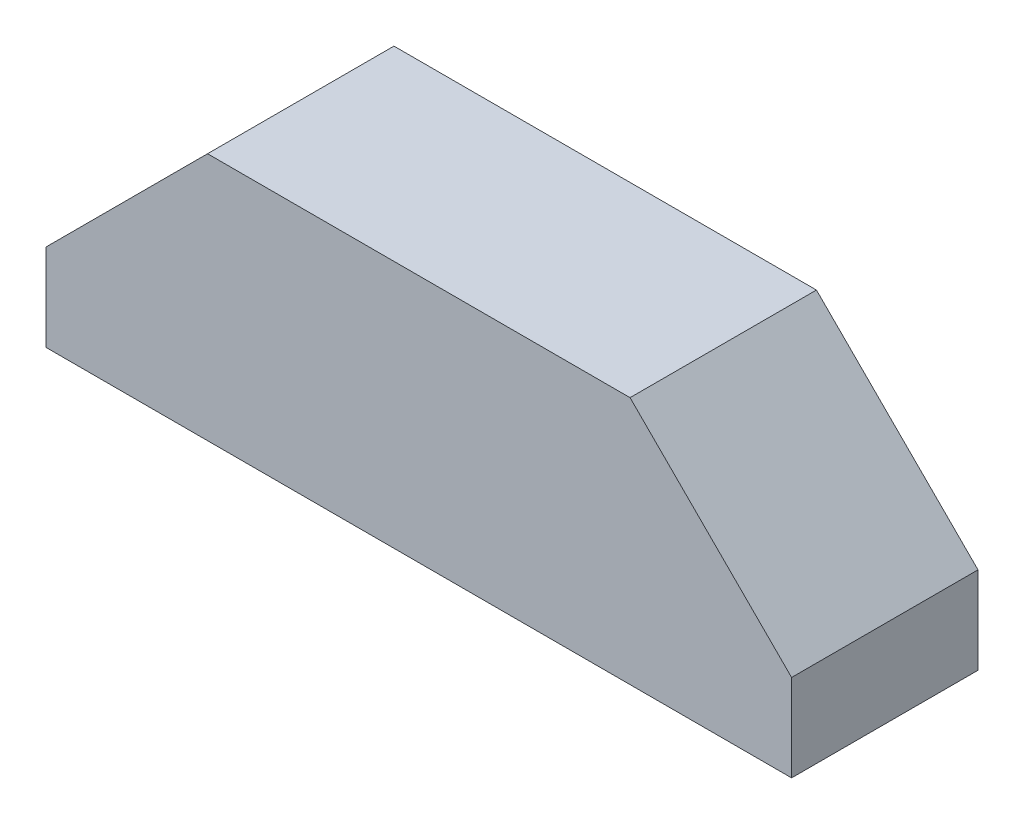
SolidWorks part; units mm, degrees
ref_plane "Ebene vorne" through (0, 0, 0) normal (0, 0, 1) x (1, 0, 0)
ref_plane "Ebene oben" through (0, 0, 0) normal (0, 1, 0) x (1, 0, 0)
ref_plane "Ebene rechts" through (0, 0, 0) normal (1, 0, 0) x (0, 0, -1)
sketch "Skizze1" plane through (0, 0, 0) normal (0, 0, 1) x (1, 0, 0)
  line L0 (0, 0) -> (0, 23680.6173) construction
  line L1 (3.4, 1.8089) -> (-3.4, 1.8089)
  line L2 (-3.4, 1.8089) -> (-6, -0.7911)
  line L3 (-6, -0.7911) -> (-6, -2.1911)
  line L4 (-6, -2.1911) -> (6, -2.1911)
  line L5 (6, -0.7911) -> (6, -2.1911)
  line L6 (3.4, 1.8089) -> (6, -0.7911)
  point P9 (0, -2.1911)
  point P11 (0, 1.8089)
  dimension "D1" = 3.4
  dimension "D2" = 6
  dimension "D3" = 4
  dimension "D4" = 135
extrude "Aufsatz-Linear austragen1" add sketch "Skizze1" along normal blind 3 contours L1 L2 L3 L4 L5 L6
